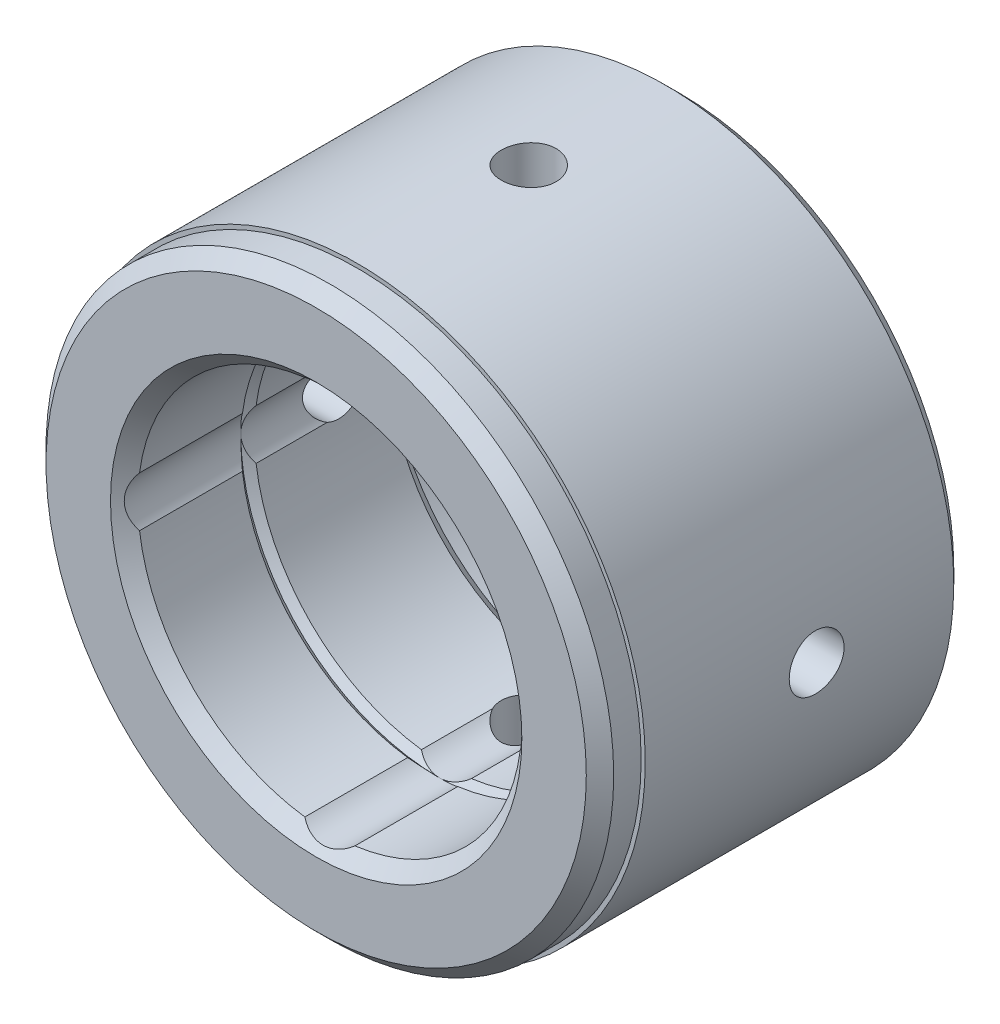
SolidWorks part; units mm, degrees
material "PB01 (C90710) Bronze"
ref_plane "Front" through (0, 0, 0) normal (0, 0, 1) x (1, 0, 0)
ref_plane "Top" through (0, 0, 0) normal (0, 1, 0) x (1, 0, 0)
ref_plane "Right" through (0, 0, 0) normal (1, 0, 0) x (0, 0, -1)
sketch "Sketch1" plane through (0, 0, 0) normal (1, 0, 0) x (0, 0, -1)
  line L0 (0, 0) -> (26.5, 0) construction
  line L1 (3, 21) -> (25.5, 21)
  line L2 (26.5, 20) -> (26.5, 19)
  line L3 (0, 19.7) -> (0, 15)
  line L4 (3, 21) -> (3, 20.7)
  line L5 (1, 20.7) -> (3, 20.7)
  line L6 (0, 19.7) -> (1, 20.7)
  line L7 (0, 20.7) -> (26.5, 20.7) construction
  line L8 (0, 21) -> (26.5, 21) construction
  line L9 (3, 21) -> (3, 0) construction
  line L10 (0, 21) -> (0, 0) construction
  line L11 (26.5, 21) -> (26.5, 0) construction
  line L12 (25.5, 21) -> (26.5, 20)
  line L13 (1, 14) -> (8.5, 14)
  line L14 (20.3, 18) -> (20.3, 15)
  line L15 (20.3, 18) -> (25.5, 18)
  line L16 (0, 14) -> (26.5, 14) construction
  line L17 (20.3, 20) -> (20.3, 0) construction
  line L18 (9, 14.5) -> (8.5, 14)
  line L19 (0, 18) -> (26.5, 18) construction
  line L20 (26.5, 20) -> (26.5, 0) construction
  line L21 (9.5, 14) -> (19.3, 14)
  line L22 (9, 14.5) -> (9.5, 14)
  line L23 (0, 15) -> (1, 14)
  line L24 (19.3, 14) -> (20.3, 15)
  line L25 (25.5, 18) -> (26.5, 19)
  point P18 (20.3, 14)
  point P22 (0, 14.5)
  point P23 (26.5, 14.5)
  point P24 (9, 19.7)
  point P25 (9, 14)
  dimension "D1" = 26.5
  dimension "D2" = 21
  dimension "D3" = 20.7
  dimension "D4" = 3
  dimension "D6" = 45
  dimension "D8" = 45
  dimension "D9" = 14
  dimension "D10" = 18
  dimension "D11" = 6.2
  dimension "D12" = 9
  dimension "D13" = 14.5
  dimension "D14" = 90
  dimension "D15" = 45
  dimension "D17" = 45
  dimension "D18" = 1
  dimension "D19" = 45
  dimension "D21" = 45
revolve "Revolve1" add sketch "Sketch1" angle 360 about L0
ref_plane "Plane1" through (0, 21, 0) normal (0, 1, 0) x (1, 0, 0)
hole_wizard "Ø4.0 (4) Diameter Hole1" positions "Sketch3" profile "Sketch2" hole size "Ø4.0" standard "ISO"
sketch "Sketch3" plane through (0, 21, 0) normal (0, 1, 0) x (1, 0, 0)
  line L0 (19, 26.5) -> (-19, 26.5) construction
  point P0 (0, 15.5)
  dimension "D1" = 11
sketch "Sketch2" plane through (0, 21, -15.5) normal (1, 0, 0) x (0, 0, 1)
  line L0 (0, 0) -> (0, 11.2017)
  line L1 (0, 11.2017) -> (2, 10)
  line L2 (2, 10) -> (2, 0)
  line L5 (2, 0) -> (0, 0)
  line L10 (0, 11.2017) -> (-2, 10) construction
  line L11 (0, -6.35) -> (0, 107.95) construction
  dimension "Hole Dia." = 4
  dimension "Hole Depth" = 10
  dimension "Drill Angle" = 118
sketch "Sketch4" plane through (0, 0, 0) normal (0, 0, 1) x (1, 0, 0)
  line L0 (0, 0) -> (0, 15) construction
  circle A0 centre (0, 0) radius 15 construction
  circle A1 centre (0, 11.5) radius 3
  circle A2 centre (0, 0) radius 14 construction
  dimension "D1" = 6
  dimension "D2" = 0.5
extrude "Cut-Extrude1" cut sketch "Sketch4" against normal blind 15.5
pattern_circular "CirPattern1" count 4 over 360 about axis through (0, 0, 0) along (0, 0, 1) of "Ø4.0 (4) Diameter Hole1", "Cut-Extrude1"
